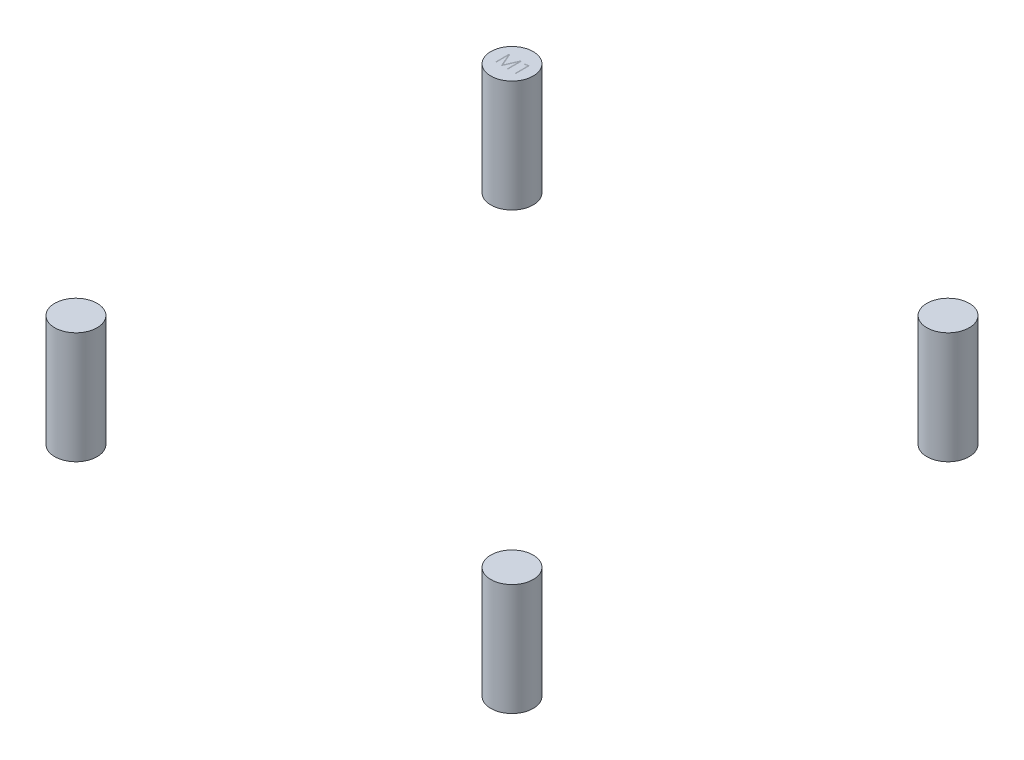
SolidWorks part; units mm, degrees
ref_plane "Front Plane" through (0, 0, 0) normal (0, 0, 1) x (1, 0, 0)
ref_plane "Top Plane" through (0, 0, 0) normal (0, 1, 0) x (1, 0, 0)
ref_plane "Right Plane" through (0, 0, 0) normal (1, 0, 0) x (0, 0, -1)
sketch "Sketch1" plane through (0, 0, 0) normal (0, 1, 0) x (1, 0, 0)
  line L0 (0, 0) -> (-146.318, -39.8387) construction
  circle A0 centre (-30.445, 30.445) radius 2.96
  circle A1 centre (30.445, 30.445) radius 2.96
  circle A2 centre (30.445, -30.445) radius 2.96
  circle A3 centre (-30.445, -30.445) radius 2.96
  point P15 (0, 0)
  dimension "D1" = 4
extrude "Boss-Extrude1" add sketch "Sketch1" along normal blind 15.6
sketch "Sketch2" plane through (0, 0, 0) normal (0, 1, 0) x (1, 0, 0)
  text T0 "M1" font "Roboto Thin" height in points 5
split line "Split Line1"
